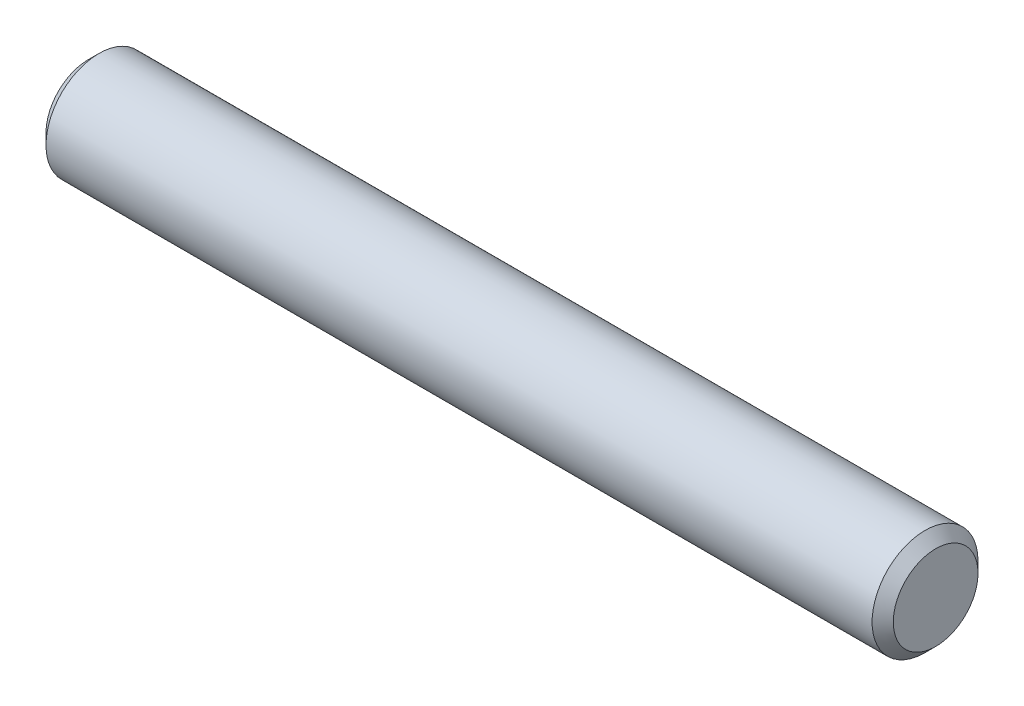
SolidWorks part; units mm, degrees
material "AISI 316 Stainless Steel Sheet (SS)"
ref_plane "Front" through (0, 0, 0) normal (0, 0, 1) x (1, 0, 0)
ref_plane "Top" through (0, 0, 0) normal (0, 1, 0) x (1, 0, 0)
ref_plane "Right" through (0, 0, 0) normal (1, 0, 0) x (0, 0, -1)
sketch "Sketch1" plane through (0, 0, 0) normal (0, 0, 1) x (1, 0, 0)
  line L0 (-6.35, 0) -> (6.35, 0) construction
  line L1 (6.35, 0.7937) -> (6.35, -0.7937) construction
  line L2 (-6.35, 0.7937) -> (-6.35, -0.7937) construction
  dimension "Length" = 12.7
  dimension "Diameter" = 1.5875
sketch "Sketch2" plane through (0, 0, 0) normal (1, 0, 0) x (0, 0, -1)
  circle A0 centre (0, 0) radius 0.7937
extrude "Extrude1" add sketch "Sketch2" against normal up to vertex (6.35 mm away) and the other way up to vertex (6.35 mm away) up to point (-6.35, 0.7937, 0) other way up to point (6.35, 0.7937, 0)
chamfer "Chamfer1" distance 0.1588 angle 45 2 edges at (6.35, 0, -0.7937) (-6.35, 0, -0.7937)
equation "\"D1@Chamfer1\" = \"Diameter@Sketch1\"*.1"
